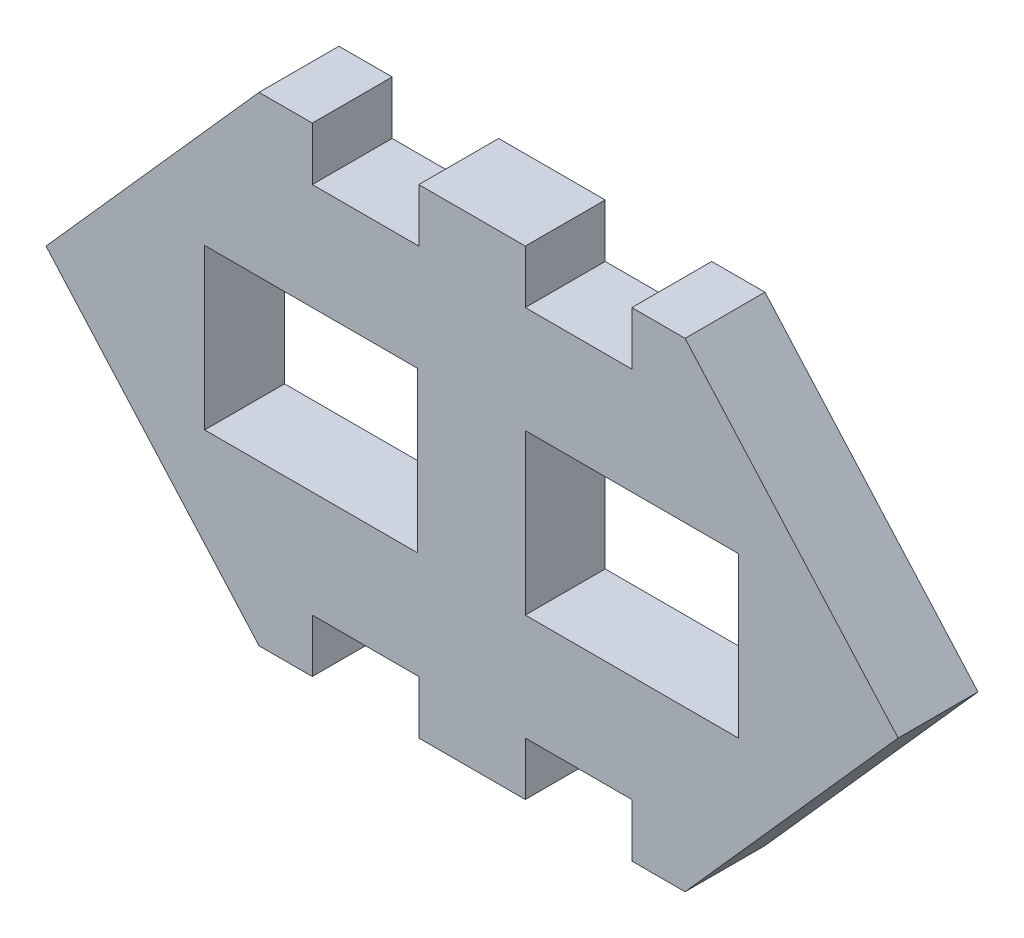
SolidWorks part; units mm, degrees
ref_plane "Front Plane" through (0, 0, 0) normal (0, 0, 1) x (1, 0, 0)
ref_plane "Top Plane" through (0, 0, 0) normal (0, 1, 0) x (1, 0, 0)
ref_plane "Right Plane" through (0, 0, 0) normal (1, 0, 0) x (0, 0, -1)
sketch "Sketch1" plane through (0, 0, 0) normal (0, 0, 1) x (1, 0, 0)
  line L0 (0, 0) -> (101.6, 114.3)
  line L1 (101.6, 114.3) -> (127, 114.3)
  line L2 (127, 114.3) -> (127, 88.9)
  line L3 (127, 88.9) -> (177.8, 88.9)
  line L4 (177.8, 88.9) -> (177.8, 114.3)
  line L5 (177.8, 114.3) -> (228.6, 114.3)
  line L6 (228.6, 114.3) -> (228.6, 88.9)
  line L7 (228.6, 88.9) -> (279.4, 88.9)
  line L8 (279.4, 88.9) -> (279.4, 114.3)
  line L9 (279.4, 114.3) -> (304.8, 114.3)
  line L10 (304.8, 114.3) -> (406.4, 0)
  line L11 (406.4, 0) -> (304.8, -114.3)
  line L12 (304.8, -114.3) -> (279.4, -114.3)
  line L13 (279.4, -114.3) -> (279.4, -88.9)
  line L14 (279.4, -88.9) -> (228.6, -88.9)
  line L15 (228.6, -88.9) -> (228.6, -114.3)
  line L16 (228.6, -114.3) -> (177.8, -114.3)
  line L17 (177.8, -114.3) -> (177.8, -88.9)
  line L18 (177.8, -88.9) -> (127, -88.9)
  line L19 (127, -88.9) -> (127, -114.3)
  line L20 (127, -114.3) -> (101.6, -114.3)
  line L21 (101.6, -114.3) -> (0, 0)
  line L23 (177.2831, 38.1) -> (75.6831, 38.1)
  line L24 (177.2831, 38.1) -> (177.2831, -38.1)
  line L25 (177.2831, -38.1) -> (75.6831, -38.1)
  line L26 (75.6831, 38.1) -> (75.6831, -38.1)
  line L27 (228.6, 38.1) -> (330.2, 38.1)
  line L28 (228.6, 38.1) -> (228.6, -38.1)
  line L29 (228.6, -38.1) -> (330.2, -38.1)
  line L30 (330.2, 38.1) -> (330.2, -38.1)
  point P3 (203.2, 114.3)
  dimension "D1" = 25.4
  dimension "D2" = 25.4
  dimension "D3" = 50.8
  dimension "D4" = 50.8
  dimension "D5" = 50.8
  dimension "D6" = 50.8
  dimension "D7" = 25.4
  dimension "D8" = 25.4
  dimension "D9" = 50.8
  dimension "D10" = 50.8
  dimension "D11" = 25.4
  dimension "D12" = 25.4
  dimension "D13" = 25.4
  dimension "D14" = 25.4
  dimension "D15" = 101.6
  dimension "D16" = 101.6
  dimension "D17" = 114.3
  dimension "D18" = 114.3
  dimension "D19" = 25.4
  dimension "D20" = 25.4
  dimension "4.5" = 114.3
  dimension "D21" = 25.4
  dimension "D22" = 50.8
  dimension "D23" = 50.8
  dimension "D24" = 101.6
  dimension "D25" = 101.6
  dimension "D26" = 76.2
  dimension "D27" = 76.2
extrude "Boss-Extrude1" add sketch "Sketch1" along normal blind 38.1
